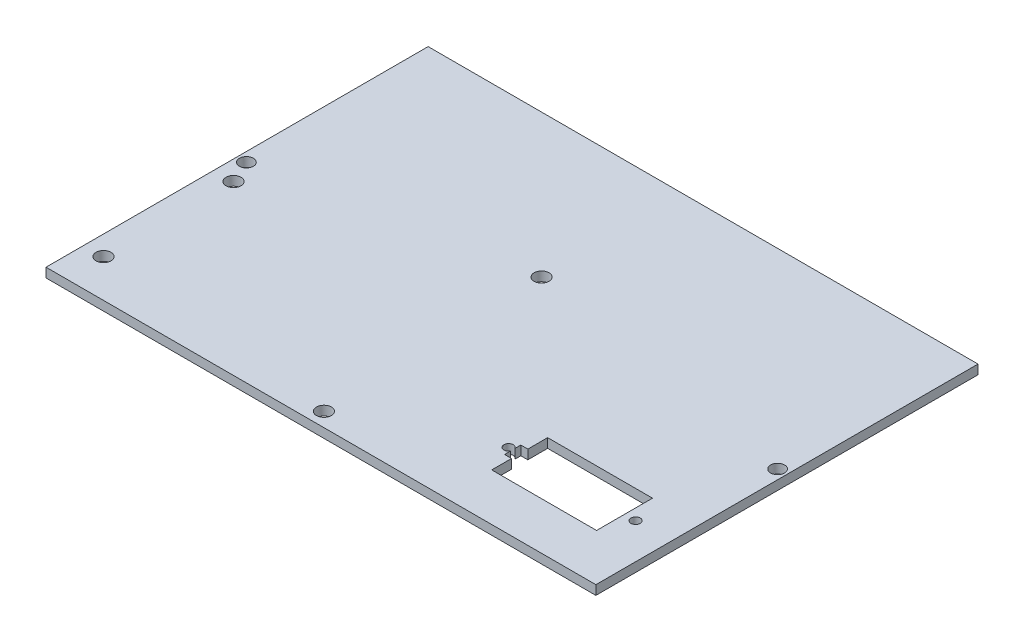
SolidWorks part; units mm, degrees
ref_plane "Front Plane" through (0, 0, 0) normal (0, 0, 1) x (1, 0, 0)
ref_plane "Top Plane" through (0, 0, 0) normal (0, 1, 0) x (1, 0, 0)
ref_plane "Right Plane" through (0, 0, 0) normal (1, 0, 0) x (0, 0, -1)
sketch "Sketch1" plane through (0, 0, 0) normal (0, 1, 0) x (1, 0, 0)
  line L1 (-59, -41) -> (59, -41)
  line L2 (-59, -41) -> (-59, 41)
  line L3 (-59, 41) -> (59, 41)
  line L4 (59, -41) -> (59, 41)
  line L5 (-59, -41) -> (59, 41) construction
  line L6 (-59, 41) -> (59, -41) construction
  point P0 (0, 0)
  dimension "D1" = 118
  dimension "D2" = 82
extrude "Boss-Extrude1" add sketch "Sketch1" along normal blind 2
sketch "Sketch3" plane through (0, 2, 0) normal (0, 1, 0) x (1, 0, 0)
  line L0 (0, 0) -> (-59, 0) construction
  line L1 (-59, 41) -> (-59, -41) construction
  line L2 (-58.5, 0) -> (-59, 0) construction
  line L3 (0, 41) -> (0, -41) construction
  line L4 (59, 41) -> (-59, 41) construction
  line L5 (-59, -41) -> (59, -41) construction
  circle A0 centre (-57, 0) radius 1.5
  circle A1 centre (57, 0) radius 1.5
  dimension "D1" = 2
  dimension "D2" = 3
extrude "Cut-Extrude5" cut sketch "Sketch3" against normal blind 10
sketch "Sketch4" plane through (0, 0, 0) normal (0, -1, 0) x (1, 0, 0)
  circle A0 centre (-2.4, 37.9606) radius 1.6
  circle A1 centre (-54.8, 32.8606) radius 1.6
  circle A2 centre (-4, -10.3394) radius 1.6
  circle A3 centre (-54.8, 4.9606) radius 1.6
extrude "Cut-Extrude6" cut sketch "Sketch4" against normal blind 10
sketch "Sketch5" plane through (0, 2, 0) normal (0, 1, 0) x (1, 0, 0)
  line L0 (48.8, -30.85) -> (49.2, -30.85) construction
  line L1 (49, -30.85) -> (26.5, -30.85)
  line L2 (49, -30.85) -> (49, -18.85)
  line L3 (49, -18.85) -> (26.5, -18.85)
  line L4 (26.5, -30.85) -> (26.5, -18.85)
  line L5 (26.7, -18.85) -> (26.3, -18.85) construction
sketch "Sketch7" plane through (0, 2, 0) normal (0, 1, 0) x (1, 0, 0)
  line L0 (26.5, -24.85) -> (24.7066, -24.85) construction
  line L1 (26.5, -23.1) -> (25, -23.1)
  line L2 (26.5, -23.1) -> (26.5, -26.6)
  line L3 (26.5, -26.6) -> (25, -26.6)
  line L4 (25, -23.1) -> (25, -26.6)
  line L5 (26.5, -30.85) -> (26.5, -18.85) construction
  line L6 (25.75, -23.1) -> (25.75, -26.6) construction
  line L7 (25, -24.85) -> (26.5, -24.85) construction
  circle A0 centre (24.125, -24.85) radius 1
  circle A1 centre (51.375, -24.85) radius 1
  point P12 (25.75, -24.85)
  dimension "D1" = 3.5
  dimension "D2" = 1.5
extrude "Cut-Extrude7" cut sketch "Sketch7" against normal blind 10 contours A0 | L2 L1 L4 L3 | A1
extrude "Cut-Extrude8" cut sketch "Sketch5" against normal blind 10 contours L3 L4 L1 L2
